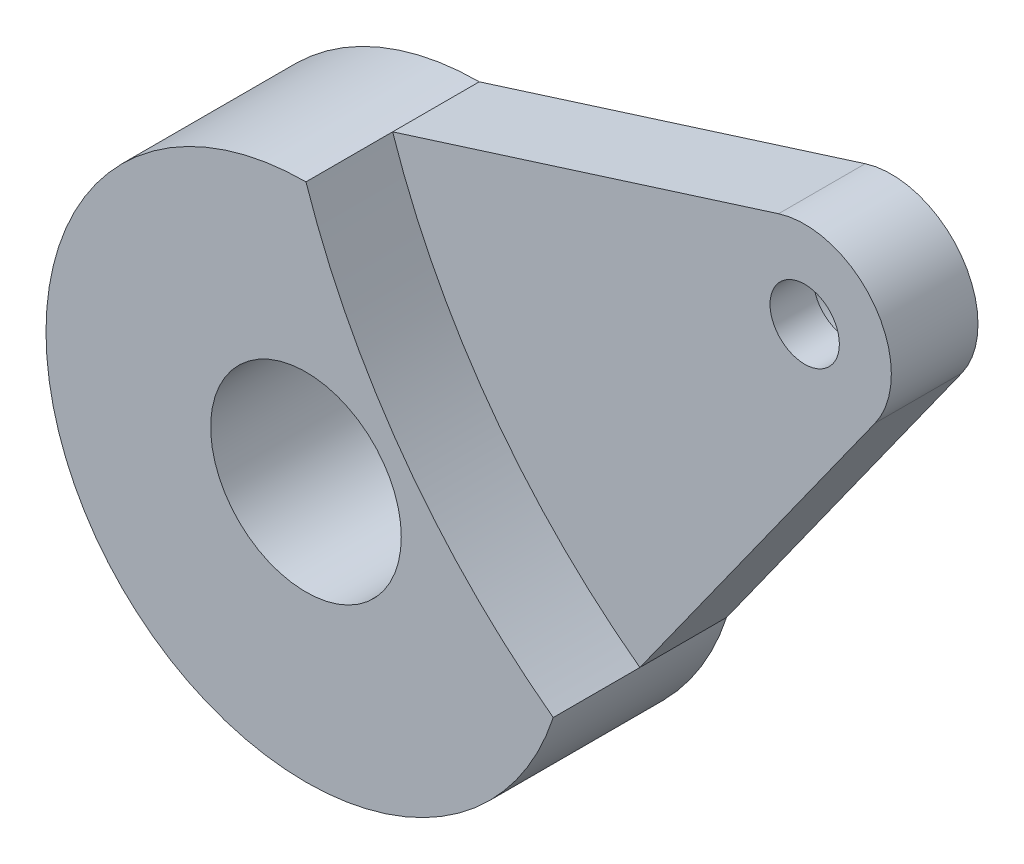
SolidWorks part; units mm, degrees
ref_plane "Ön Düzlem" through (0, 0, 0) normal (0, 0, 1) x (1, 0, 0)
ref_plane "Üst Düzlem" through (0, 0, 0) normal (0, 1, 0) x (1, 0, 0)
ref_plane "Sağ Düzlem" through (0, 0, 0) normal (1, 0, 0) x (0, 0, -1)
sketch "Sketch1" plane through (0, 0, 0) normal (0, 0, 1) x (1, 0, 0)
  line L0 (-121.3146, 100) -> (121.3146, 100) construction
  line L1 (-91.3643, 0) -> (91.3643, 0) construction
  line L2 (0, 100) -> (0, -76.3006) construction
  line L3 (0, 0) -> (47.5528, 34.5492) construction
  line L4 (47.5528, 34.5492) -> (0, 100) construction
  line L5 (0, 0) -> (55.9017, -18.1636) construction
  line L6 (44.5378, 44.0838) -> (0, 30)
  line L7 (55.6891, 28.7353) -> (28.5317, -9.2705)
  line L8 (17.9307, 82.1257) -> (50.7307, 36.9803)
  line L9 (11.4586, 77.4234) -> (44.2586, 32.2781)
  circle A2 centre (47.5528, 34.5492) radius 4
  circle A3 centre (0, 0) radius 58.7785 construction
  circle A4 centre (47.5528, 34.5492) radius 10
  circle A5 centre (0, 100) radius 80.9017
  circle A6 centre (0, 0) radius 30
  circle A7 centre (14.6946, 79.7746) radius 4
  circle A8 centre (0, 0) radius 58.778 construction
  circle A9 centre (0, 100) radius 25 construction
  arc A10 (28.5317, -9.2705) -> (0, 30) centre (76.7005, 55.7262) cw
  point P4 (0, 0)
  point P6 (0, 0)
  point P30 (12.1798, 100)
  dimension "D4" = 8
  dimension "D6" = 20
  dimension "D7" = 60
  dimension "D8" = 117.556
  dimension "D9" = 50
  dimension "D10" = 80.9
  dimension "D1" = 100
  dimension "D2" = 36
  dimension "D3" = 54
  dimension "D5" = 252
sketch "Sketch2" plane through (0, 0, 0) normal (0, 0, 1) x (1, 0, 0)
  line L0 (44.5378, 44.0838) -> (0, 30) construction
  line L1 (55.6891, 28.7353) -> (28.5317, -9.2705) construction
  line L2 (44.5378, 44.0838) -> (0, 30)
  line L3 (55.6891, 28.7353) -> (28.5317, -9.2705)
  circle A0 centre (47.5528, 34.5492) radius 10 construction
  circle A1 centre (0, 0) radius 30 construction
  arc A2 (55.6891, 28.7353) -> (44.5378, 44.0838) centre (47.5528, 34.5492) ccw
  arc A3 (0, 30) -> (28.5317, -9.2705) centre (0, 0) ccw
  circle A4 centre (47.5528, 34.5492) radius 4 construction
  circle A5 centre (47.5528, 34.5492) radius 4
  circle A6 centre (0, 0) radius 11
  dimension "D1" = 22
extrude "Boss-Extrude1" add sketch "Sketch2" along normal blind 20
sketch "Sketch3" plane through (0, 0, 0) normal (0, 0, -1) x (-1, 0, 0)
  circle A0 centre (-47.5528, 34.5492) radius 7.5
  dimension "D1" = 15
extrude "Cut-Extrude1" cut sketch "Sketch3" against normal blind 5
sketch "Sketch4" plane through (0, 0, 0) normal (0, 0, -1) x (-1, 0, 0)
  circle A0 centre (0, 0) radius 20
  circle A1 centre (0, 0) radius 16
  dimension "D1" = 32
  dimension "D2" = 40
extrude "Boss-Extrude2" add sketch "Sketch4" along normal blind 10
sketch "Sketch5" plane through (0, 0, 20) normal (0, 0, 1) x (1, 0, 0)
  line L0 (44.5378, 44.0838) -> (0, 30) construction
  line L1 (28.5317, -9.2705) -> (55.6891, 28.7353) construction
  line L2 (44.5378, 44.0838) -> (0, 30)
  line L3 (28.5317, -9.2705) -> (55.6891, 28.7353)
  arc A0 (0, 30) -> (28.5317, -9.2705) centre (76.7005, 55.7262) ccw construction
  arc A1 (0, 30) -> (28.5317, -9.2705) centre (76.7005, 55.7262) ccw
  arc A2 (55.6891, 28.7353) -> (44.5378, 44.0838) centre (47.5528, 34.5492) ccw construction
  arc A3 (55.6891, 28.7353) -> (44.5378, 44.0838) centre (47.5528, 34.5492) ccw
extrude "Cut-Extrude2" cut sketch "Sketch5" against normal blind 10
